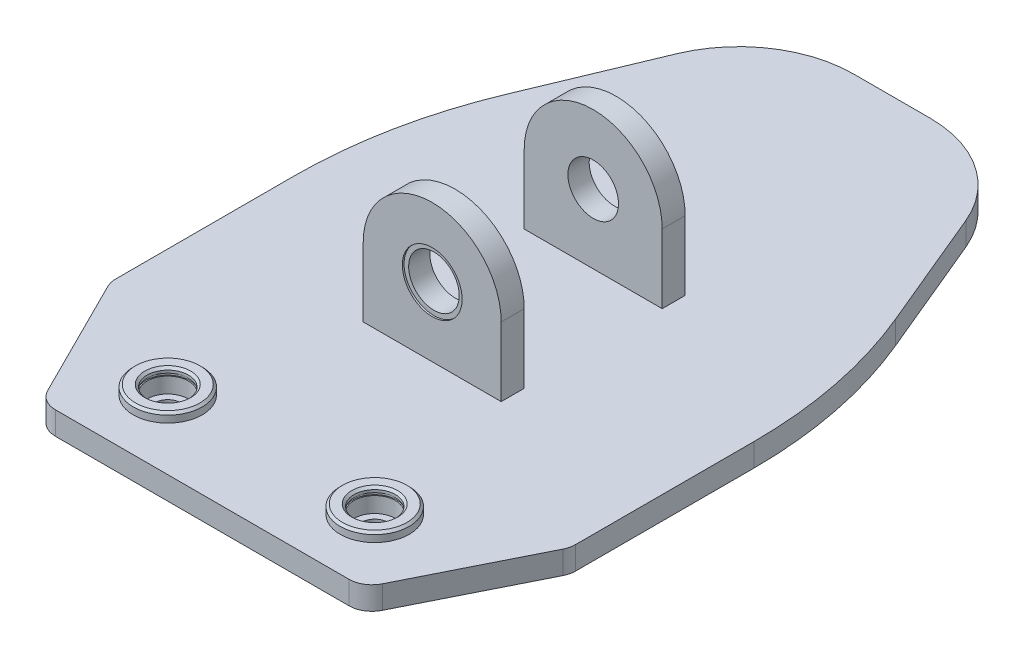
SolidWorks part; units mm, degrees
material "6061 合金"
ref_plane "前视基准面" through (0, 0, 0) normal (0, 0, 1) x (1, 0, 0)
ref_plane "上视基准面" through (0, 0, 0) normal (0, 1, 0) x (1, 0, 0)
ref_plane "右视基准面" through (0, 0, 0) normal (1, 0, 0) x (0, 0, -1)
other "Configuration Table"
sketch "草图1" plane through (0, 0, 0) normal (0, 1, 0) x (1, 0, 0)
  line L0 (0, 0) -> (0, 255.8207) construction
  line L1 (-100, 0) -> (100, 0)
  line L2 (100, 0) -> (100, 180)
  line L3 (100, 180) -> (50, 300)
  line L4 (50, 300) -> (-50, 300)
  line L5 (-100, 180) -> (-50, 300)
  line L6 (-100, 0) -> (-100, 180)
  point P8 (0, 300)
  dimension "D1" = 300
  dimension "D2" = 100
  dimension "D3" = 120
  dimension "D4" = 50
extrude "凸台-拉伸1" add sketch "草图1" along normal blind 10
sketch "草图2" plane through (100, 0, 0) normal (1, 0, 0) x (0, 0, -1)
  line L0 (40, 100) -> (40, -10.3339) construction
  line L1 (0, 10) -> (0, 0) construction
  line L2 (0, 10) -> (0, 60)
  line L3 (80, 10) -> (80, 60)
  arc A0 (80, 60) -> (0, 60) centre (40, 60) ccw
  circle A1 centre (40, 60) radius 10
  line M6 (180, 10) -> (0, 10)
  dimension "D3" = 20
  dimension "D1" = 40
  dimension "D2" = 50
extrude "凸台-拉伸2" [suppressed] add sketch "草图2" against normal up to surface (200 mm away) contours A0 L0 A1 L3 M6 | L0 A0 L2 A1 M6
sketch "草图3" [suppressed] plane through (0, 10, 0) normal (0, 1, 0) x (1, 0, 0)
  line L0 (0, 0) -> (0, 135.8056) construction
  line L1 (-100, 0) -> (100, 0) construction
  line L2 (-70, 0) -> (70, 0)
  line L3 (-70, 0) -> (-70, 100)
  line L4 (-70, 100) -> (70, 100)
  line L5 (70, 0) -> (70, 100)
  line L6 (100, 0) -> (100, 80) construction
  line L7 (-100, 80) -> (-100, 0) construction
  dimension "D1" = 30
  dimension "D2" = 30
  dimension "D3" = 100
extrude "切除-拉伸1" [suppressed] cut sketch "草图3" along normal blind 171
sketch "草图4" plane through (0, 0, 0) normal (0, 0, 1) x (1, 0, 0)
  line L0 (0, 0) -> (0, 92.3322) construction
  line L1 (30, 40) -> (30, 10)
  line L2 (-30, 40) -> (-30, 10)
  line L3 (-100, 10) -> (100, 10) construction
  arc A0 (-30, 40) -> (30, 40) centre (0, 40) cw
  circle A1 centre (0, 40) radius 11
  line M10 (100, 10) -> (-100, 10)
  dimension "D2" = 30
  dimension "D3" = 22
  dimension "D1" = 30
extrude "凸台-拉伸3" add sketch "草图4" against normal blind 80 from offset 100 contours L0 L1 A0 A1 M10 | L0 A1 A0 L2 M10 offset against normal yes
sketch "草图5" plane through (0, 10, 0) normal (0, 1, 0) x (1, 0, 0)
  line L0 (-47.074, 140) -> (51.1394, 140) construction
  line L1 (30, 180) -> (-30, 180) construction
  line L2 (30, 100) -> (-30, 100) construction
  line L3 (-30, 100) -> (30, 100) construction
  line L4 (-40, 170) -> (40, 170)
  line L5 (-40, 170) -> (-40, 110)
  line L6 (-40, 110) -> (40, 110)
  line L7 (40, 170) -> (40, 110)
  line L8 (30, 180) -> (30, 100) construction
  line L9 (-30, 180) -> (-30, 100) construction
  dimension "D1" = 10
  dimension "D2" = 10
  dimension "D3" = 10
  dimension "D4" = 10
extrude "切除-拉伸2" cut sketch "草图5" along normal blind 110 contours L7 L6 L5 L4
fillet "圆角1" radius 50 2 edges at (-50, 5, -300) (50, 5, -300)
fillet "圆角2" radius 200 2 edges at (-100, 5, -180) (100, 5, -180)
sketch "草图6" [suppressed] plane through (100, 0, 0) normal (1, 0, 0) x (0, 0, -1)
  line L0 (40, 60) -> (40, -52.2503) construction
  circle A0 centre (40, 60) radius 10 construction
  circle A1 centre (40, 60) radius 10 construction
  arc A2 (73.0468, 82.5368) -> (6.9532, 82.5368) centre (40, -25) ccw
  arc A3 (80, 60) -> (0, 60) centre (40, 60) ccw construction
  arc A4 (73.0468, 82.5368) -> (6.9532, 82.5368) centre (40, 60) ccw
  dimension "D2" = 225
  dimension "D1" = 25
extrude "切除-拉伸3" [suppressed] cut sketch "草图6" against normal through all both and the other way through all contours A2 A4
sketch "草图7" plane through (0, 10, 0) normal (0, 1, 0) x (1, 0, 0)
  line L0 (0, 0) -> (0, 141.3983) construction
  line L1 (-100, 0) -> (100, 0) construction
  circle A0 centre (45, 30) radius 9
  dimension "D1" = 18
  dimension "D2" = 45
  dimension "D3" = 30
extrude "切除-拉伸6" cut sketch "草图7" against normal offset from surface (6 mm away) 4 contours A0 up to face at (0, 0, -186.7805)
sketch "草图10" plane through (0, 4, 0) normal (0, 1, 0) x (1, 0, 0)
  circle A0 centre (45, 30) radius 6
  dimension "D1" = 12
extrude "切除-拉伸7" cut sketch "草图10" against normal blind 28 contours A0
sketch "草图11" plane through (0, 10, 0) normal (0, 1, 0) x (1, 0, 0)
  circle A0 centre (45, 30) radius 12.5
  circle A1 centre (45, 30) radius 16.5
  dimension "D1" = 25
  dimension "D2" = 33
extrude "切除-拉伸8" [suppressed] cut sketch "草图11" against normal blind 5
sketch "草图12" plane through (0, 10, 0) normal (0, 1, 0) x (1, 0, 0)
  circle A0 centre (45, 30) radius 15
  dimension "D1" = 30
extrude "凸台-拉伸5" add sketch "草图12" along normal blind 4 contours A0
sketch "草图13" plane through (0, 14, 0) normal (0, 1, 0) x (1, 0, 0)
  circle A0 centre (45, 30) radius 9
  dimension "D1" = 18
extrude "切除-拉伸9" cut sketch "草图13" against normal blind 4
sketch "草图14" plane through (0, 14, 0) normal (0, 1, 0) x (1, 0, 0)
  circle A0 centre (45, 30) radius 9.5
  circle A2 centre (45, 30) radius 9 construction
  circle A3 centre (45, 30) radius 9
  dimension "D1" = 19
extrude "卡簧槽" cut sketch "草图14" against normal blind 1.1 from offset 2.15 contours A0 offset against normal yes
chamfer "倒角1" distance 1 angle 45 2 edges at (45, 14, -15) (45, 14, -21)
ref_plane "基准面1" through (0, 0, 0) normal (-1, 0, 0) x (0, 0, 1)
mirror "镜向1" about plane through (0, 0, 0) normal (-1, 0, 0) of "切除-拉伸6", "切除-拉伸7", "凸台-拉伸5", "切除-拉伸9", "卡簧槽", "倒角1"
sketch "草图16" plane through (0, 0, -100) normal (0, 0, 1) x (1, 0, 0)
  circle A0 centre (0, 40) radius 13
  dimension "D1" = 26
extrude "切除-拉伸10" cut sketch "草图16" against normal blind 0.75
sketch "草图17" plane through (0, 0, -180) normal (0, 0, -1) x (-1, 0, 0)
  circle A0 centre (0, 40) radius 13
  dimension "D1" = 26
extrude "切除-拉伸11" cut sketch "草图17" against normal blind 0.75 contours A0
sketch "草图18" plane through (-100, 0, 0) normal (-1, 0, 0) x (0, 0, 1)
  line L0 (-30, 92.2697) -> (-30, -20.0308) construction
  line L1 (-40, 10) -> (-40, 30)
  line L2 (-140, 10) -> (0, 10) construction
  line L3 (-20, 30) -> (-20, 10)
  line L4 (-40, 10) -> (-20, 10)
  arc A0 (-20, 30) -> (-40, 30) centre (-30, 30) ccw
  circle A1 centre (-30, 30) radius 2.5
  dimension "D2" = 5
  dimension "D4" = 10
  dimension "D1" = 30
  dimension "D3" = 20
extrude "凸台-拉伸6" [suppressed] add sketch "草图18" against normal up to surface (200 mm away) contours A1 L0 | L0 A1 | L3 L4 L1 A0
sketch "草图20" plane through (0, 10, 0) normal (0, 1, 0) x (1, 0, 0)
  line L0 (0, 0) -> (0, 309.5578) construction
  line L1 (-100, 0) -> (100, 0) construction
  line L2 (-60.0864, 49.2403) -> (-60.0864, 11.6041)
  line L3 (75.0864, 51.8093) -> (107.8414, 51.8093)
  line L4 (75.0864, 51.8093) -> (75.0864, 7.1083)
  line L5 (75.0864, 7.1083) -> (107.8414, 7.1083)
  line L6 (107.8414, 51.8093) -> (107.8414, 7.1083)
  line L7 (15, 49.2403) -> (60.0864, 49.2403)
  line L8 (15, 49.2403) -> (15, 11.6041)
  line L9 (15, 11.6041) -> (60.0864, 11.6041)
  line L10 (60.0864, 49.2403) -> (60.0864, 11.6041)
  line L11 (-15, 11.6041) -> (-60.0864, 11.6041)
  line L12 (-15, 49.2403) -> (-15, 11.6041)
  line L13 (-15, 49.2403) -> (-60.0864, 49.2403)
  line L14 (-107.8414, 51.8093) -> (-107.8414, 7.1083)
  line L15 (-75.0864, 7.1083) -> (-107.8414, 7.1083)
  line L16 (-75.0864, 51.8093) -> (-75.0864, 7.1083)
  line L17 (-75.0864, 51.8093) -> (-107.8414, 51.8093)
  dimension "D1" = 15
  dimension "D2" = 15
extrude "切除-拉伸12" [suppressed] cut sketch "草图20" along normal through all
chamfer "倒角2" distance 30 distance2 60 1 edges at (100, 5, 0)
chamfer "倒角3" distance 60 distance2 30 1 edges at (-100, 5, 0)
fillet "圆角3" radius 10 4 edges at (-70, 5, 0) (-100, 5, -60) (70, 5, 0) (100, 5, -60)
ref_plane "脚底板中心面" through (0, 0, 0) normal (-1, 0, 0) x (0, 0, 1)
ref_plane "基准面3" through (0, 0, -30) normal (0, 0, 1) x (1, 0, 0)
sketch "草图22" plane through (0, 0, -30) normal (0, 0, 1) x (1, 0, 0)
  line L0 (45, 18.5577) -> (45, -23.1228) construction
  line L1 (-45, 24.8334) -> (-45, -23.1228) construction
  line L2 (45, 0) -> (45, 4) construction
  line L3 (-45, 0) -> (-45, 4) construction
ref_plane "基准面4" through (-45, 0, 0) normal (-1, 0, 0) x (0, 0, 1)
